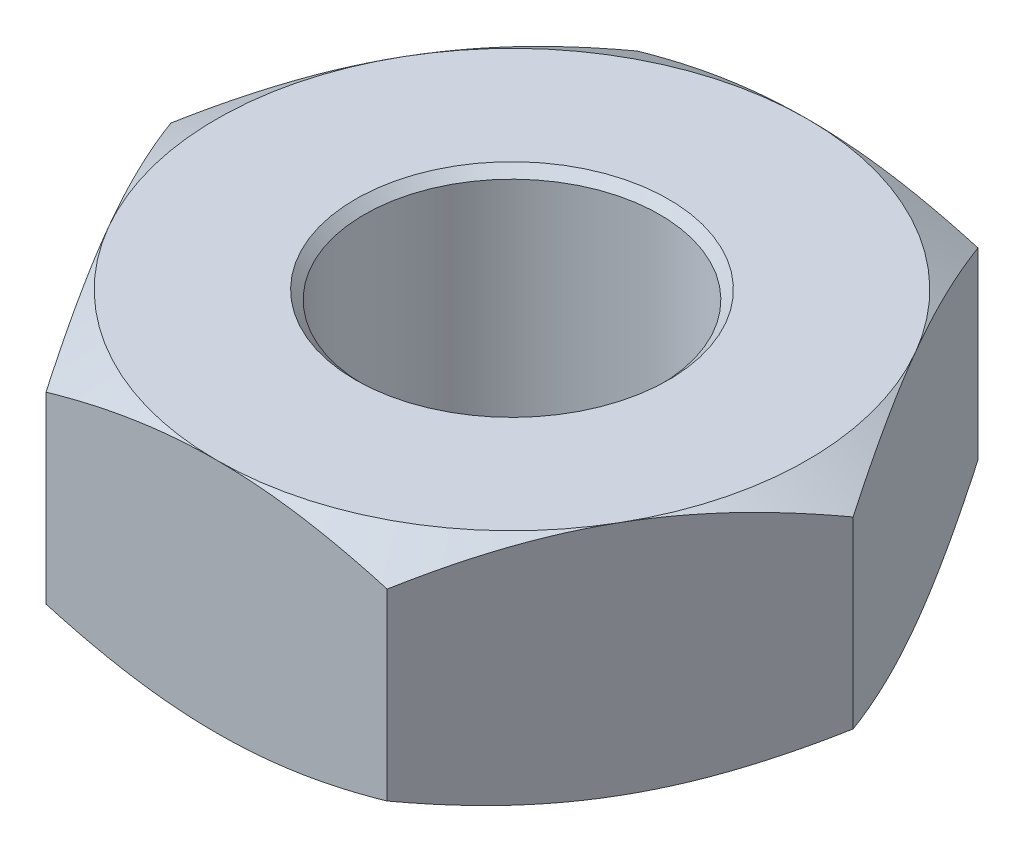
SolidWorks part; units mm, degrees
ref_plane "Front Plane" through (0, 0, 0) normal (0, 0, 1) x (1, 0, 0)
ref_plane "Top Plane" through (0, 0, 0) normal (0, 1, 0) x (1, 0, 0)
ref_plane "Right Plane" through (0, 0, 0) normal (1, 0, 0) x (0, 0, -1)
sketch "Sketch2" plane through (0, 0, 0) normal (0, 1, 0) x (1, 0, 0)
  line L1 (2.8868, 0) -> (1.4434, 2.5)
  line L2 (1.4434, 2.5) -> (-1.4434, 2.5)
  line L3 (-1.4434, 2.5) -> (-2.8868, 0)
  line L4 (-2.8868, 0) -> (-1.4434, -2.5)
  line L5 (-1.4434, -2.5) -> (1.4434, -2.5)
  line L6 (1.4434, -2.5) -> (2.8868, 0)
  circle A0 centre (0, 0) radius 1.25
  circle A1 centre (0, 0) radius 2.5 construction
  dimension "D1" = 2.5
  dimension "D2" = 5
extrude "Boss-Extrude1" add sketch "Sketch2" along normal blind 2
sketch "Sketch3" plane through (0, 0, 0) normal (0, 1, 0) x (1, 0, 0)
  circle A0 centre (0, 0) radius 2.5 construction
  circle A1 centre (0, 0) radius 2.5
extrude "Cut-Extrude1" cut sketch "Sketch3" along normal blind 3.25 draft 60 flip side to cut
sketch "Sketch4" plane through (0, 2, 0) normal (0, 1, 0) x (1, 0, 0)
  circle A1 centre (0, 0) radius 2.5
  circle A2 centre (0, 0) radius 2.5
  dimension "D1" = 0
extrude "Cut-Extrude2" cut sketch "Sketch4" against normal blind 3.25 draft 60 flip side to cut
chamfer "Chamfer1" distance 0.075 angle 45 2 edges at (0, 0, 1.25) (0, 2, 1.25)
